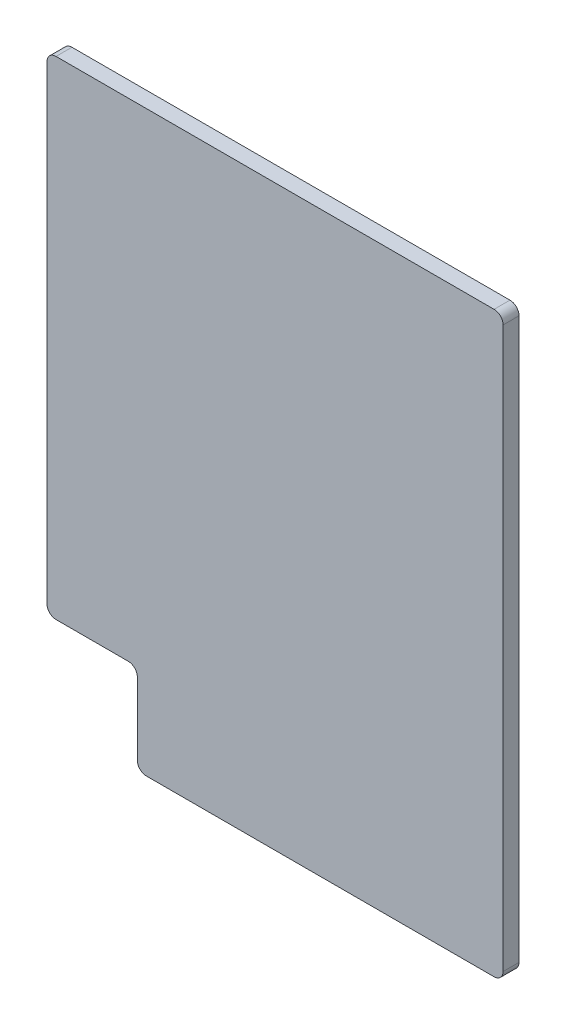
SolidWorks part; units mm, degrees
material "Acrylic (Medium-high impact)"
ref_plane "Front Plane" through (0, 0, 0) normal (0, 0, 1) x (1, 0, 0)
ref_plane "Top Plane" through (0, 0, 0) normal (0, 1, 0) x (1, 0, 0)
ref_plane "Right Plane" through (0, 0, 0) normal (1, 0, 0) x (0, 0, -1)
sketch "Sketch1" plane through (0, 0, 0) normal (0, 0, 1) x (1, 0, 0)
  line L1 (0, 0) -> (160.3375, 0)
  line L2 (0, 0) -> (0, 203.2)
  line L3 (0, 203.2) -> (160.3375, 203.2)
  line L4 (160.3375, 0) -> (160.3375, 203.2)
  line L5 (0, 0) -> (31.75, 0)
  line L6 (0, 0) -> (0, 31.75)
  line L7 (0, 31.75) -> (31.75, 31.75)
  line L8 (31.75, 0) -> (31.75, 31.75)
  dimension "D1" = 160.3375
  dimension "D2" = 203.2
  dimension "D3" = 31.75
  dimension "D4" = 31.75
extrude "Boss-Extrude1" add sketch "Sketch1" along normal blind 5.588 contours L8 L1 L4 L3 L2 L7
fillet "Fillet1" radius 3.175 6 edges at (160.3375, 0, 2.794) (31.75, 0, 2.794) (31.75, 31.75, 2.794) (0, 31.75, 2.794) (160.3375, 203.2, 2.794) (0, 203.2, 2.794)
